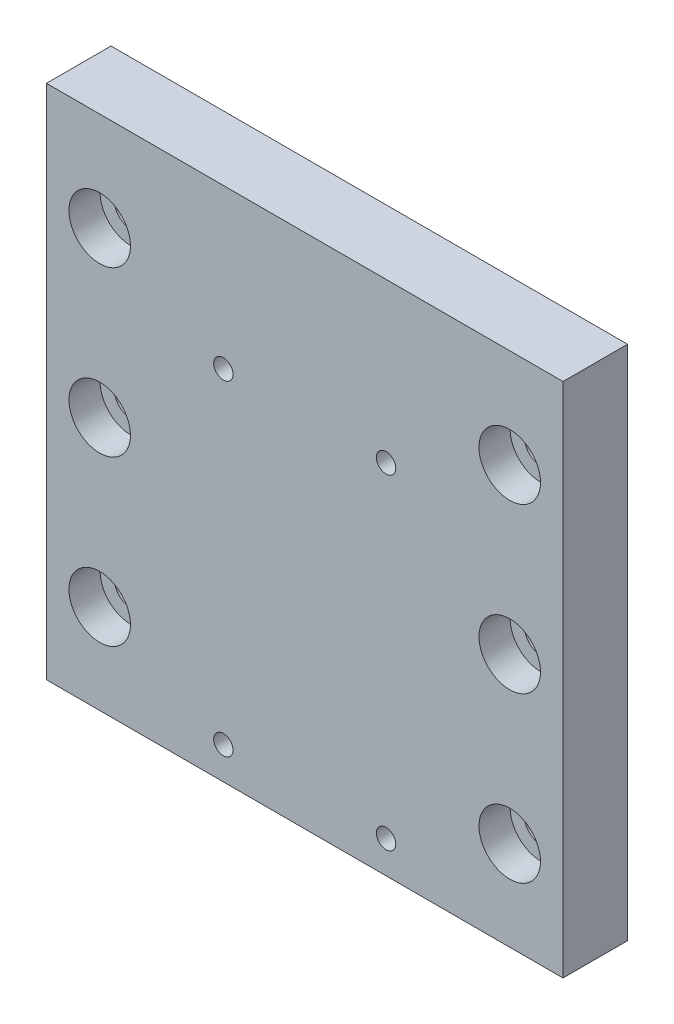
SolidWorks part; units mm, degrees
ref_plane "Front" through (0, 0, 0) normal (0, 0, 1) x (1, 0, 0)
ref_plane "Top" through (0, 0, 0) normal (0, 1, 0) x (1, 0, 0)
ref_plane "Right" through (0, 0, 0) normal (1, 0, 0) x (0, 0, -1)
sketch "Sketch1" plane through (0, 0, 0) normal (0, 0, 1) x (1, 0, 0)
  line L1 (-55.7364, 59.3851) -> (24.2636, 59.3851)
  line L2 (-55.7364, 59.3851) -> (-55.7364, -20.6149)
  line L3 (-55.7364, -20.6149) -> (24.2636, -20.6149)
  line L4 (24.2636, 59.3851) -> (24.2636, -20.6149)
  dimension "D1" = 80
  dimension "D2" = 80
extrude "Extrude1" add sketch "Sketch1" along normal blind 10
hole_wizard "CBORE for #10 Socket Head Cap Screw2" positions "3DSketch2" profile "Sketch3" counterbore size "#10" standard "Ansi Inch" end condition through all
sketch3d "3DSketch2"
  line L0 (-55.7364, 59.3851, 10) -> (-55.7364, -20.6149, 10) construction
  point P0 (-47.4864, 44.0779, 10)
  point P2 (-47.4864, 18.6779, 10)
  point P4 (-47.4864, -6.7221, 10)
  point P6 (16.0136, -6.7221, 10)
  point P8 (16.0136, 18.6779, 10)
  point P10 (16.0136, 44.0779, 10)
  dimension "D1" = 63.5
  dimension "D2" = 25.4
  dimension "D3" = 25.4
  dimension "D4" = 25.4
  dimension "D5" = 25.4
  dimension "D6" = 8.25
sketch "Sketch3" plane through (-47.4864, 44.0779, 10) normal (1, 0, 0) x (0, -1, 0)
  line L0 (0, 0) -> (0, 10)
  line L1 (0, 10) -> (2.5527, 10)
  line L3 (2.5527, 10) -> (2.5527, 4.826)
  line L4 (2.5527, 4.826) -> (4.7625, 4.826)
  line L5 (4.7625, 4.826) -> (4.7625, 0)
  line L7 (4.7625, 0) -> (0, 0)
  line L11 (0, -6.35) -> (0, 107.95) construction
  dimension "Thru Hole Dia." = 5.1054
  dimension "Thru Hole Depth" = 10
  dimension "C'Bore Dia." = 9.525
  dimension "C'Bore Depth" = 4.826
hole_wizard "M3x0.5 Tapped Hole1" positions "3DSketch3" profile "Sketch4" tap size "M3x0.5" standard "Ansi Metric"
sketch3d "3DSketch3"
  line L0 (-55.7364, -20.6149, 10) -> (24.2636, -20.6149, 10) construction
  line L1 (-55.7364, 59.3851, 10) -> (-55.7364, -20.6149, 10) construction
  point P0 (-28.3364, 34.7851, 10)
  point P4 (-28.3364, -15.6149, 10)
  dimension "D1" = 50.4
  dimension "D2" = 5
  dimension "D3" = 27.4
sketch "Sketch4" plane through (-28.3364, 34.7851, 10) normal (1, 0, 0) x (0, -1, 0)
  line L0 (0, 0) -> (0, 8.2511)
  line L1 (0, 8.2511) -> (1.25, 7.5)
  line L2 (1.25, 7.5) -> (1.25, 6)
  line L3 (1.25, 6) -> (1.5, 6)
  line L4 (1.5, 6) -> (1.5, 0)
  line L5 (1.5, 0) -> (0, 0)
  line L10 (0, 8.2511) -> (-1.25, 7.5) construction
  line L11 (0, -6.35) -> (0, 107.95) construction
  dimension "Tap Drill Dia." = 2.5
  dimension "Tap Drill Depth" = 7.5
  dimension "Thread Major Dia." = 3
  dimension "Thread Depth" = 6
  dimension "Drill Angle" = 118
pattern_linear "LPattern4" count 2 spacing 25.2 along (1, 0, 0) of "M3x0.5 Tapped Hole1"
